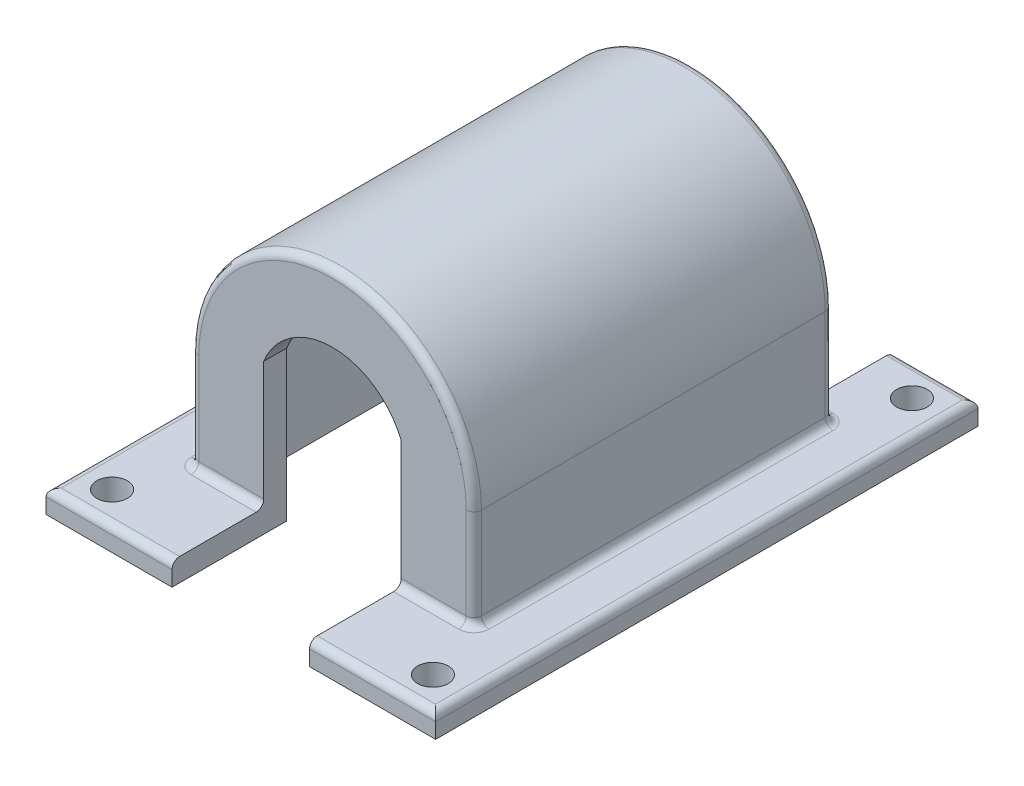
SolidWorks part; units mm, degrees
material "ABS"
ref_plane "Plan de face" through (0, 0, 0) normal (0, 0, 1) x (1, 0, 0)
ref_plane "Plan de dessus" through (0, 0, 0) normal (0, 1, 0) x (1, 0, 0)
ref_plane "Plan de droite" through (0, 0, 0) normal (1, 0, 0) x (0, 0, -1)
sketch "Esquisse1" plane through (0, 0, 0) normal (0, 0, 1) x (1, 0, 0)
  line L0 (-18.5, 0) -> (-14.5, 0)
  line L1 (14.5, 0) -> (18.5, 0)
  arc A0 (18.5, 0) -> (-18.5, 0) centre (0, 0) ccw
  arc A1 (14.5, 0) -> (-14.5, 0) centre (0, 0) ccw
  point P1 (0, 0)
  dimension "D1" = 14.5
  dimension "D2" = 4
extrude "Boss.-Extru.1" add sketch "Esquisse1" along normal blind 3
sketch "Esquisse3" plane through (0, 0, 3) normal (0, 0, 1) x (1, 0, 0)
  line L0 (-18.5, 0) -> (-16.25, 0)
  line L1 (18.5, 0) -> (16.25, 0)
  arc A2 (16.25, 0) -> (-16.25, 0) centre (0, 0) ccw
  arc A3 (18.5, 0) -> (-18.5, 0) centre (0, 0) ccw
  arc A4 (18.5, 0) -> (-18.5, 0) centre (0, 0) ccw construction
  dimension "D1" = 32.5
extrude "Boss.-Extru.2" add sketch "Esquisse3" along normal blind 44
sketch "Esquisse4" plane through (0, 0, 47) normal (0, 0, 1) x (1, 0, 0)
  line L1 (9, 0) -> (18.5, 0)
  line L2 (9, 0) -> (9, 3.618)
  line L3 (-9, 3.618) -> (-9, 0)
  line L4 (-9, 0) -> (-18.5, 0)
  arc A2 (9, 3.618) -> (-9, 3.618) centre (0, 0) ccw
  arc A3 (-18.5, 0) -> (18.5, 0) centre (0, 0) cw
  arc A4 (18.5, 0) -> (-18.5, 0) centre (0, 0) ccw construction
  point P15 (-7.9981, 0.1757)
  dimension "D1" = 9.7
  dimension "D2" = 18
extrude "Boss.-Extru.4" add sketch "Esquisse4" against normal blind 3
sketch "Esquisse6" plane through (0, 0, 0) normal (0, -1, 0) x (1, 0, 0)
  line L0 (14.5, 3) -> (16.25, 3) construction
  line L1 (14.5, 3) -> (14.5, 0) construction
  line L2 (14.5, 0) -> (18.5, 0) construction
  line L3 (18.5, 47) -> (18.5, 0) construction
  line L4 (16.25, 44) -> (16.25, 3) construction
  line L5 (9, 44) -> (16.25, 44) construction
  line L6 (9, 47) -> (18.5, 47) construction
  line L7 (9, 44) -> (9, 47) construction
  line L8 (-14.5, 3) -> (-14.5, 0) construction
  line L9 (-18.5, 0) -> (-14.5, 0) construction
  line L10 (-16.25, 3) -> (-14.5, 3) construction
  line L11 (-16.25, 44) -> (-16.25, 3) construction
  line L12 (-16.25, 44) -> (-9, 44) construction
  line L13 (-9, 44) -> (-9, 47) construction
  line L14 (-18.5, 47) -> (-9, 47) construction
  line L15 (-18.5, 47) -> (-18.5, 0) construction
  line L16 (14.5, 3) -> (16.25, 3)
  line L17 (14.5, 3) -> (14.5, 0)
  line L18 (14.5, 0) -> (18.5, 0)
  line L19 (18.5, 47) -> (18.5, 0)
  line L20 (16.25, 44) -> (16.25, 3)
  line L21 (9, 44) -> (16.25, 44)
  line L22 (9, 47) -> (18.5, 47)
  line L23 (9, 44) -> (9, 47)
  line L24 (-14.5, 3) -> (-14.5, 0)
  line L25 (-18.5, 0) -> (-14.5, 0)
  line L26 (-16.25, 3) -> (-14.5, 3)
  line L27 (-16.25, 44) -> (-16.25, 3)
  line L28 (-16.25, 44) -> (-9, 44)
  line L29 (-9, 44) -> (-9, 47)
  line L30 (-18.5, 47) -> (-9, 47)
  line L31 (-18.5, 47) -> (-18.5, 0)
extrude "Boss.-Extru.6" add sketch "Esquisse6" along normal blind 16
sketch "Esquisse10" plane through (18.5, 0, 0) normal (1, 0, 0) x (0, 0, -1)
  line L5 (0, -16) -> (-47, -16) construction
  line L6 (12, -16) -> (-59, -16)
  line L7 (12, -16) -> (12, -13)
  line L8 (12, -13) -> (-59, -13)
  line L9 (-59, -16) -> (-59, -13)
  line L10 (0, -16) -> (0, 0) construction
  line L11 (-47, -16) -> (-47, 0) construction
  dimension "D1" = 3
  dimension "D2" = 12
  dimension "D3" = 12
extrude "Boss.-Extru.10" add sketch "Esquisse10" along normal blind 7
mirror "Symétrie4" about plane through (0, 0, 0) normal (1, 0, 0) of "Boss.-Extru.10"
sketch "Esquisse12" plane through (0, -16, 0) normal (0, -1, 0) x (1, 0, 0)
  line L0 (-21, 54.85) -> (-21, -7.85) construction
  line L1 (-21, 54.85) -> (21, 54.85) construction
  line L2 (-21, -7.85) -> (21, -7.85) construction
  line L3 (21, 54.85) -> (21, -7.85) construction
  line L4 (0, 0) -> (0, 54.85) construction
  line L5 (-21, 23.5) -> (-25.5, 23.5) construction
  line L7 (-25.5, -12) -> (-25.5, 59) construction
  circle A0 centre (21, 54.85) radius 2
  circle A1 centre (21, -7.85) radius 2
  circle A2 centre (-21, -7.85) radius 2
  circle A3 centre (-21, 54.85) radius 2
  point P13 (0, 0)
  point P16 (0, 0)
  dimension "D3" = 4
  dimension "D1" = 62.7
  dimension "D2" = 42
extrude "Enlèv. mat.-Extru.1" cut sketch "Esquisse12" against normal through all
sketch "Esquisse13" plane through (-18.5, 0, 0) normal (1, 0, 0) x (0, 0, -1)
  line L0 (-47, -13) -> (-59, -13) construction
  line L1 (-47, -13) -> (-59, -13)
  line L2 (-47, -13) -> (-47, -16)
  line L3 (-47, -16) -> (-59, -16)
  line L4 (-59, -13) -> (-59, -16)
  point P7 (-47, -13)
extrude "Boss.-Extru.11" add sketch "Esquisse13" along normal up to surface (9.5 mm away) up to face at (-9, -6.191, 45.5)
sketch "Esquisse14" plane through (18.5, 0, 0) normal (-1, 0, 0) x (0, 0, 1)
  line L1 (59, -13) -> (47, -13)
  line L2 (59, -13) -> (59, -16)
  line L3 (59, -16) -> (47, -16)
  line L4 (47, -13) -> (47, -16)
extrude "Boss.-Extru.12" add sketch "Esquisse14" along normal up to surface (9.5 mm away) up to face at (9, -6.191, 45.5)
sketch "Esquisse15" plane through (18.5, 0, 0) normal (-1, 0, 0) x (0, 0, 1)
  line L1 (0, -13) -> (-12, -13)
  line L2 (0, -13) -> (0, -16)
  line L3 (0, -16) -> (-12, -16)
  line L4 (-12, -13) -> (-12, -16)
extrude "Boss.-Extru.13" add sketch "Esquisse15" along normal up to surface (4 mm away) up to face at (14.5, -8, 1.5)
sketch "Esquisse16" plane through (-18.5, 0, 0) normal (1, 0, 0) x (0, 0, -1)
  line L1 (12, -16) -> (0, -16)
  line L2 (12, -16) -> (12, -13)
  line L3 (12, -13) -> (0, -13)
  line L4 (0, -16) -> (0, -13)
extrude "Boss.-Extru.14" add sketch "Esquisse16" along normal up to surface (4 mm away) up to face at (-14.5, -8, 1.5)
fillet "Congé7" radius 1 18 edges at (13.75, -13, 47) (-13.75, -13, 47) (16.5, -13, 0) (-16.5, -13, 0) (18.5, -6.5, 47) (-18.5, -6.5, 47) (18.5, -6.5, 0) (-18.5, -6.5, 0) (17.25, -13, 59) (20, -13, -12) (25.5, -13, 23.5) (-20, -13, -12) (-17.25, -13, 59) (0, 18.5, 47) (0, 18.5, 0) (-25.5, -13, 23.5) (18.5, -13, 23.5) (-18.5, -13, 23.5)
